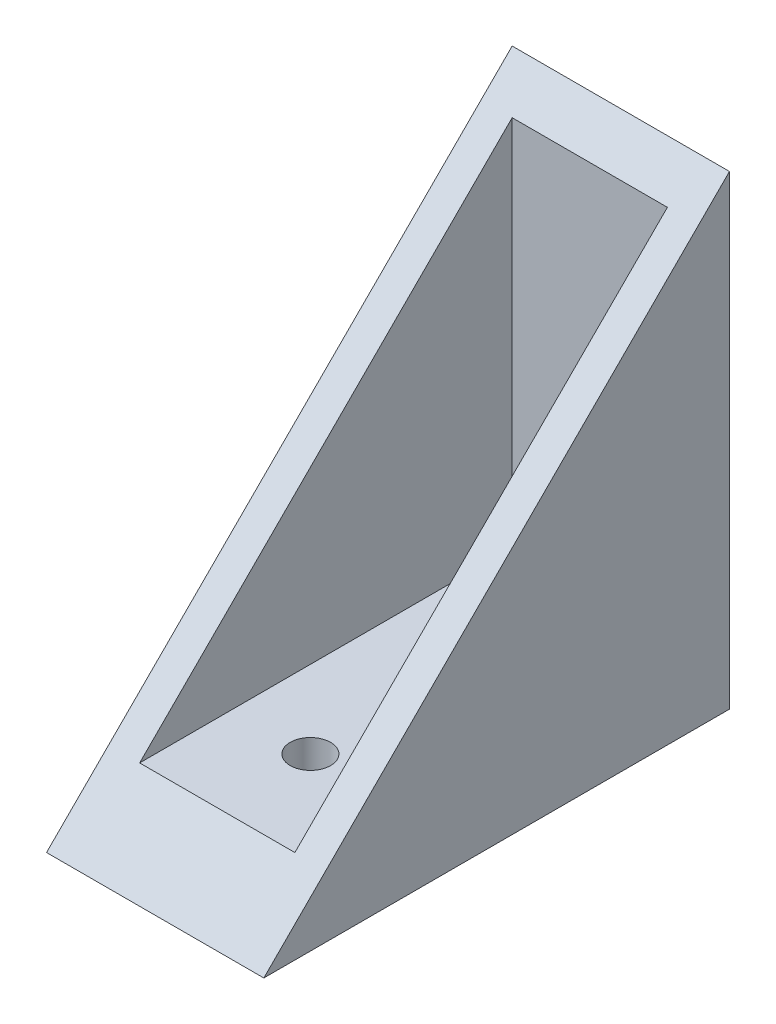
SolidWorks part; units mm, degrees
ref_plane "Front Plane" through (0, 0, 0) normal (0, 0, 1) x (1, 0, 0)
ref_plane "Top Plane" through (0, 0, 0) normal (0, 1, 0) x (1, 0, 0)
ref_plane "Right Plane" through (0, 0, 0) normal (1, 0, 0) x (0, 0, -1)
sketch "Sketch1" plane through (0, 0, 0) normal (1, 0, 0) x (0, 0, -1)
  line L0 (0, 0) -> (0, 75)
  line L1 (0, 75) -> (-75, 0)
  line L2 (-75, 0) -> (0, 0)
  dimension "D1" = 75
extrude "Boss-Extrude1" add sketch "Sketch1" along normal mid plane 35
sketch "Sketch2" plane through (0, 0, 0) normal (0, 1, 0) x (1, 0, 0)
  line L0 (17.5, -75) -> (-17.5, -75) construction
  line L1 (-12.5, -75) -> (12.5, -75)
  line L2 (-12.5, -75) -> (-12.5, -5)
  line L3 (-12.5, -5) -> (12.5, -5)
  line L4 (12.5, -75) -> (12.5, -5)
  line L5 (0, 0) -> (0, -75) construction
  line L6 (-17.5, 0) -> (-17.5, -75) construction
  dimension "D1" = 70
  dimension "D2" = 5
extrude "Cut-Extrude1" cut sketch "Sketch2" along normal through all from offset 10
hole_wizard "Ø6.0mm Dowel Hole1" positions "Sketch4" profile "Sketch5" hole size "Ø6.0" standard "ANSI Metric" end condition through all
sketch "Sketch4" plane through (0, 10, 0) normal (0, 1, 0) x (1, 0, 0)
  line L0 (0, 0) -> (0, -20) construction
  line L1 (0, -20) -> (0, -50) construction
  point P0 (0, -20)
  point P2 (0, -50)
  dimension "D1" = 20
  dimension "D2" = 30
sketch "Sketch5" plane through (0, 10, 20) normal (1, 0, 0) x (0, 0, 1)
  line L0 (0, 0) -> (0, 10)
  line L1 (0, 10) -> (3.25, 10)
  line L2 (3.25, 10) -> (3.25, 0)
  line L5 (3.25, 0) -> (0, 0)
  line L11 (0, -6.35) -> (0, 107.95) construction
  dimension "Thru Hole Dia." = 6.5
  dimension "Thru Hole Depth" = 10
